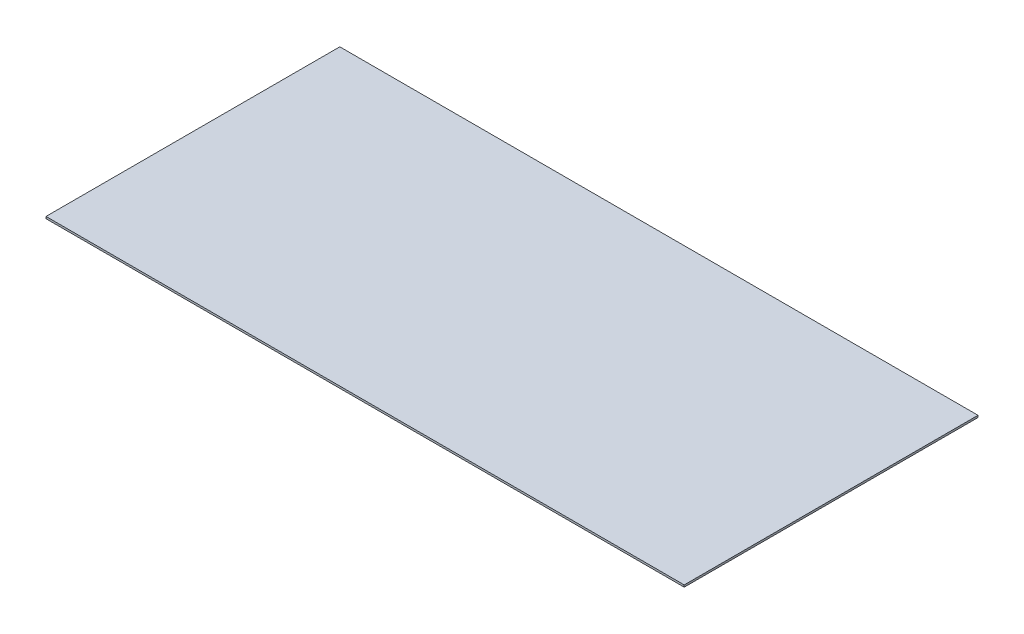
SolidWorks part; units mm, degrees
material "Custom Plastic"
ref_plane "X-Y Datum" through (0, 0, 0) normal (0, 0, 1) x (1, 0, 0)
ref_plane "X-Z Datum" through (0, 0, 0) normal (0, 1, 0) x (1, 0, 0)
ref_plane "Y-Z Datum" through (0, 0, 0) normal (1, 0, 0) x (0, 0, -1)
sketch "Sketch1" plane through (0, 0, 0) normal (0, 1, 0) x (1, 0, 0)
  line L1 (0, 0) -> (320.04, 0)
  line L2 (0, 0) -> (0, 147.32)
  line L3 (0, 147.32) -> (320.04, 147.32)
  line L4 (320.04, 0) -> (320.04, 147.32)
extrude "Boss-Extrude1" add sketch "Sketch1" along normal blind 1
